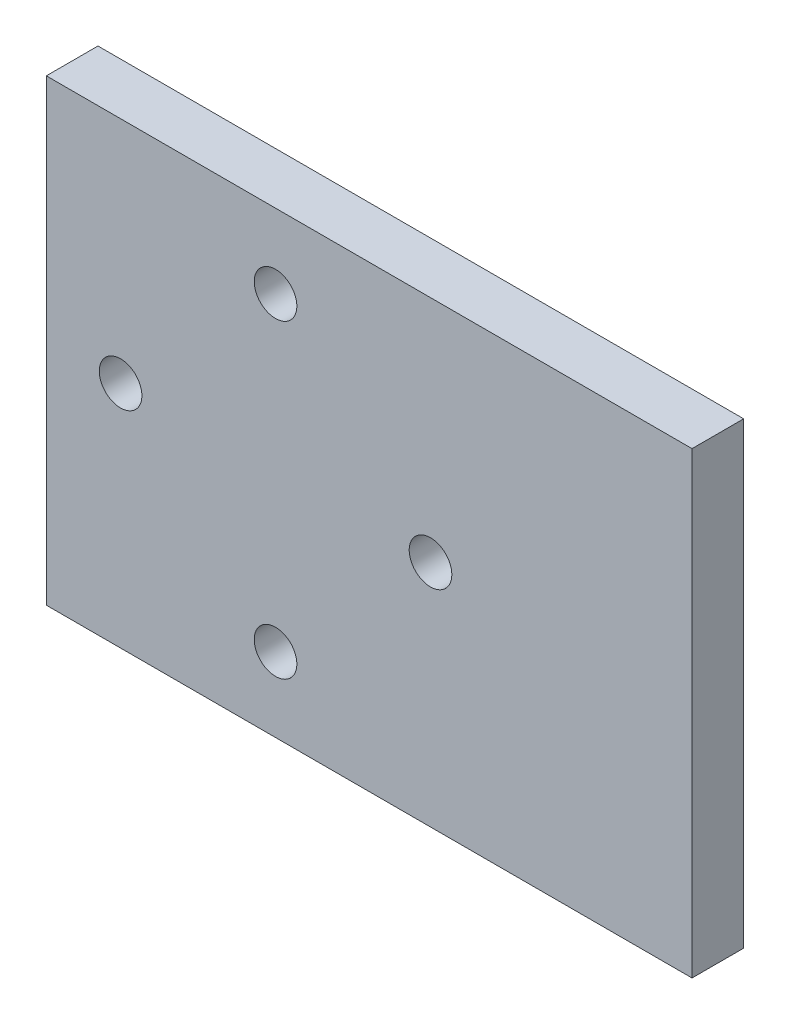
SolidWorks part; units mm, degrees
ref_plane "정면" through (0, 0, 0) normal (0, 0, 1) x (1, 0, 0)
ref_plane "윗면" through (0, 0, 0) normal (0, 1, 0) x (1, 0, 0)
ref_plane "우측면" through (0, 0, 0) normal (1, 0, 0) x (0, 0, -1)
sketch "스케치1" plane through (0, 0, 0) normal (0, 0, 1) x (1, 0, 0)
  line L1 (-50, 35.5) -> (50, 35.5)
  line L2 (-50, 35.5) -> (-50, -35.5)
  line L3 (-50, -35.5) -> (50, -35.5)
  line L4 (50, 35.5) -> (50, -35.5)
  line L5 (0, -35.5) -> (0, 35.5) construction
  line L6 (-50, 0) -> (50, 0) construction
  point P0 (0, 0)
  dimension "D1" = 100
  dimension "D2" = 71
extrude "보스-돌출1" add sketch "스케치1" along normal blind 8
sketch "스케치2" plane through (0, 0, 8) normal (0, 0, 1) x (1, 0, 0)
  line L0 (50, 35.5) -> (-50, 35.5) construction
  line L1 (-45, 30.5) -> (16, 30.5)
  line L2 (-45, 30.5) -> (-45, -30.5)
  line L3 (-45, -30.5) -> (16, -30.5)
  line L4 (16, 30.5) -> (16, -30.5)
  line L5 (-14.5, -30.5) -> (-14.5, 30.5) construction
  line L6 (-45, 0) -> (16, 0) construction
  line L7 (-50, -35.5) -> (50, -35.5) construction
  line L8 (-50, 35.5) -> (-50, -35.5) construction
  point P0 (-14.5, 0)
  point P10 (9.5, 0)
  point P11 (-38.5, 0)
  point P12 (-14.5, 24)
  point P13 (-14.5, -24)
  dimension "D1" = 5
  dimension "D2" = 5
  dimension "D3" = 5
  dimension "D4" = 61
  dimension "D5" = 6.5
  dimension "D6" = 6.5
hole_wizard "G1/16 나사 구멍1" positions "3D스케치1" profile "스케치3" tap size "G1/16" standard "KS" end condition through all
sketch3d "3D스케치1"
  point P0 (-38.5, 0, 8)
  point P3 (-14.5, -24, 8)
  point P6 (9.5, 0, 8)
  point P9 (-14.5, 24, 8)
sketch "스케치3" plane through (-38.5, 0, 8) normal (1, 0, 0) x (0, -1, 0)
  line L0 (0, 0) -> (0, 8)
  line L1 (0, 8) -> (3.3, 8)
  line L2 (3.3, 8) -> (3.3, 0)
  line L5 (3.3, 0) -> (0, 0)
  line L11 (0, -6.35) -> (0, 107.95) construction
  dimension "관통 탭 드릴 지름" = 6.6
  dimension "관통 탭 드릴 깊이" = 8
cosmetic thread "구멍 나사산1" parameters "D2"=7.723
cosmetic thread "구멍 나사산2" parameters "D2"=7.723
cosmetic thread "구멍 나사산3" parameters "D2"=7.723
cosmetic thread "구멍 나사산4" parameters "D2"=7.723
